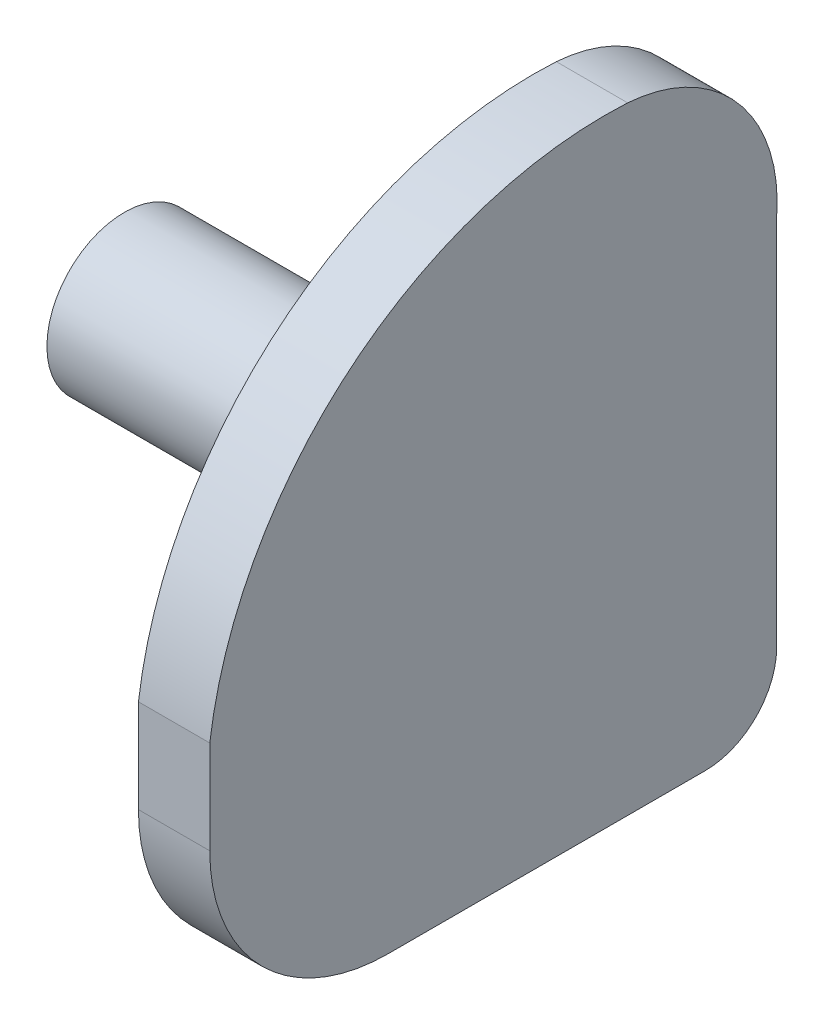
SolidWorks part; units mm, degrees
ref_plane "Front Plane" through (0, 0, 0) normal (0, 0, 1) x (1, 0, 0)
ref_plane "Top Plane" through (0, 0, 0) normal (0, 1, 0) x (1, 0, 0)
ref_plane "Right Plane" through (0, 0, 0) normal (1, 0, 0) x (0, 0, -1)
sketch "Sketch3" plane through (0, 0, 0) normal (1, 0, 0) x (0, 0, -1)
  line L2 (0, -60) -> (0, -86.1848)
  line L3 (50, -136.1848) -> (59.297, -136.1848)
  line L16 (158.939, -11.4803) -> (158.939, -50)
  line L17 (59.297, -136.1848) -> (138.939, -136.1848)
  line L18 (158.939, -50) -> (158.939, -116.1848)
  arc A1 (0, -86.1848) -> (50, -136.1848) centre (50, -86.1848) ccw
  arc A8 (0, -60) -> (117.1561, 36.8308) centre (110.8736, -74.8572) cw
  arc A13 (117.1561, 36.8308) -> (158.939, -11.4803) centre (113.892, -8.2162) cw
  arc A14 (138.939, -136.1848) -> (158.939, -116.1848) centre (138.939, -116.1848) ccw
  point P13 (0, 0)
  dimension "D1" = 20
  dimension "D2" = 50
extrude "Boss-Extrude1" add sketch "Sketch3" along normal blind 20 contours L3 L17 A14 L18 L16 A13 A8 L2 A1
scale "Scale1" scale about centroid uniform scaling yes scale factor 0.110511
sketch "Sketch5" plane through (8.8949, 0, 0) normal (-1, 0, 0) x (0, 0, 1)
  line L0 (-93.5013, -50.8771) -> (-93.5013, -62.4481) construction
  circle A0 centre (-85.5013, -55.2882) radius 2.4
  dimension "D1" = 4.8
  dimension "D3" = 8
  dimension "D2" = 9.75
extrude "Boss-Extrude2" add sketch "Sketch5" along normal blind 10
